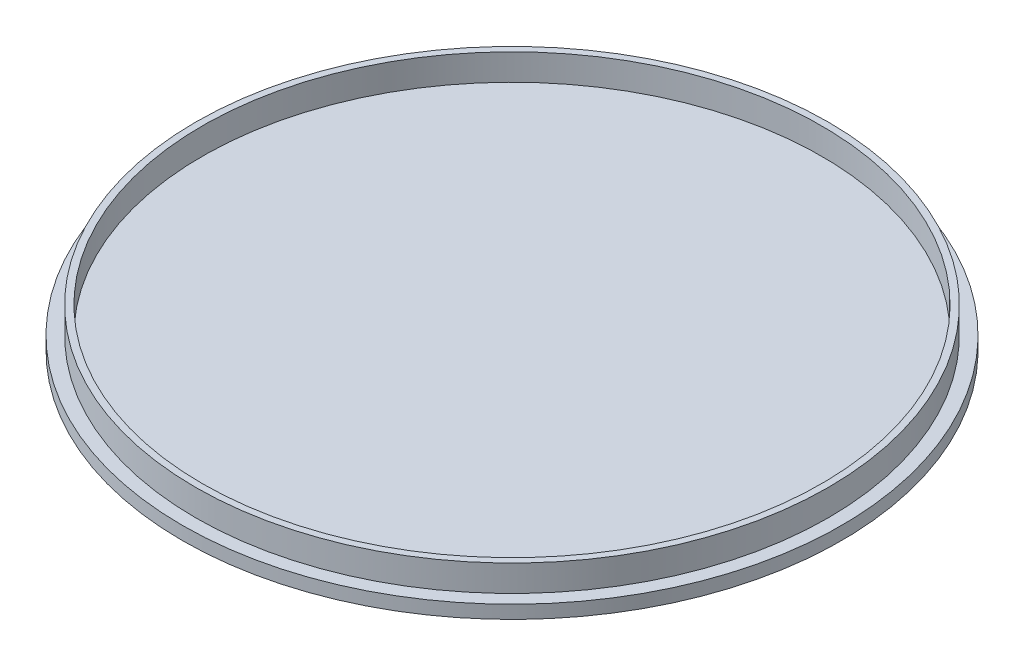
SolidWorks part; units mm, degrees
ref_plane "Front Plane" through (0, 0, 0) normal (0, 0, 1) x (1, 0, 0)
ref_plane "Top Plane" through (0, 0, 0) normal (0, 1, 0) x (1, 0, 0)
ref_plane "Right Plane" through (0, 0, 0) normal (1, 0, 0) x (0, 0, -1)
sketch "Sketch1" plane through (0, 0, 0) normal (0, 1, 0) x (1, 0, 0)
  circle A0 centre (0, 0) radius 50
  dimension "D1" = 100
extrude "Boss-Extrude1" add sketch "Sketch1" along normal blind 2
sketch "Sketch2" plane through (0, 2, 0) normal (0, 1, 0) x (1, 0, 0)
  circle A0 centre (0, 0) radius 47
  circle A1 centre (0, 0) radius 48
  dimension "D1" = 94
  dimension "D2" = 96
extrude "Boss-Extrude2" add sketch "Sketch2" along normal blind 4
sketch "Sketch3" plane through (0, 2, 0) normal (0, 1, 0) x (1, 0, 0)
  line L1 (-50, 0) -> (-61, 0) construction
  line L2 (-55.7594, 5) -> (-49.7494, 5)
  line L3 (-55.7594, -5) -> (-49.7494, -5)
  line L4 (5, 55.7594) -> (5, 49.7494)
  line L5 (-5, 55.7594) -> (-5, 49.7494)
  line L6 (55.7594, -5) -> (49.7494, -5)
  line L7 (55.7594, 5) -> (49.7494, 5)
  line L8 (-5, -55.7594) -> (-5, -49.7494)
  line L9 (5, -55.7594) -> (5, -49.7494)
  circle A0 centre (0, 0) radius 50 construction
  circle A1 centre (0, 0) radius 50
  arc A2 (-55.7594, 5) -> (-61, 0) centre (-56, 0.0058) ccw
  arc A3 (-55.7594, -5) -> (-61, 0) centre (-56, -0.0058) cw
  circle A4 centre (-56, -0.0058) radius 2.5
  circle A5 centre (-0.0058, 56) radius 2.5
  arc A6 (5, 55.7594) -> (0, 61) centre (0.0058, 56) ccw
  arc A7 (-5, 55.7594) -> (0, 61) centre (-0.0058, 56) cw
  circle A8 centre (0, 0) radius 50
  circle A9 centre (56, 0.0058) radius 2.5
  arc A10 (55.7594, -5) -> (61, 0) centre (56, -0.0058) ccw
  arc A11 (55.7594, 5) -> (61, 0) centre (56, 0.0058) cw
  circle A12 centre (0, 0) radius 50
  circle A13 centre (0.0058, -56) radius 2.5
  arc A14 (-5, -55.7594) -> (0, -61) centre (-0.0058, -56) ccw
  arc A15 (5, -55.7594) -> (0, -61) centre (0.0058, -56) cw
  circle A16 centre (0, 0) radius 50
  point P44 (0, 0)
  dimension "D4" = 5
  dimension "D1" = 11
  dimension "D2" = 6.01
  dimension "D3" = 5
  dimension "D5" = 5
  dimension "D6" = 4
